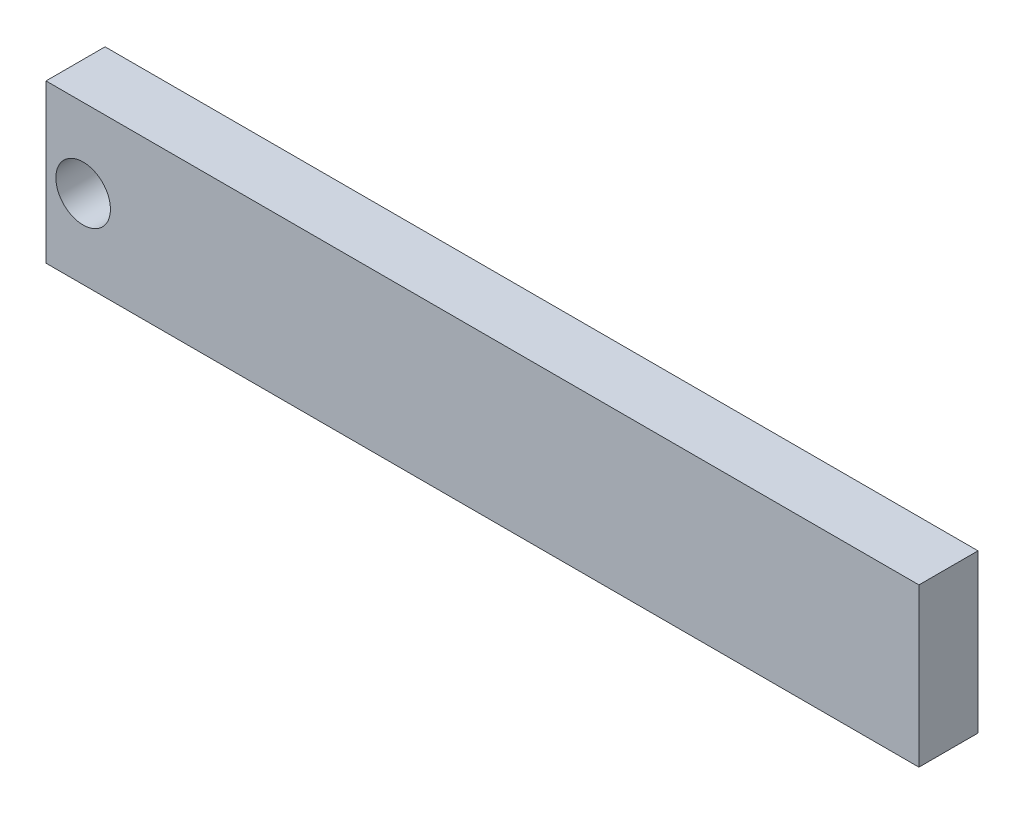
SolidWorks part; units mm, degrees
ref_plane "Front Plane" through (0, 0, 0) normal (0, 0, 1) x (1, 0, 0)
ref_plane "Top Plane" through (0, 0, 0) normal (0, 1, 0) x (1, 0, 0)
ref_plane "Right Plane" through (0, 0, 0) normal (1, 0, 0) x (0, 0, -1)
sketch "Sketch1" plane through (0, 0, 0) normal (0, 0, 1) x (1, 0, 0)
  line L0 (47, 4.25) -> (0, 4.25) construction
  line L1 (0, 0) -> (47, 0)
  line L2 (0, 0) -> (0, 8.5)
  line L3 (0, 8.5) -> (47, 8.5)
  line L4 (47, 0) -> (47, 8.5)
  circle A0 centre (2, 4.25) radius 1.47
  dimension "D3" = 2
  dimension "D4" = 2.94
  dimension "D1" = 8.5
  dimension "D2" = 47
extrude "Boss-Extrude1" add sketch "Sketch1" along normal blind 3.18
